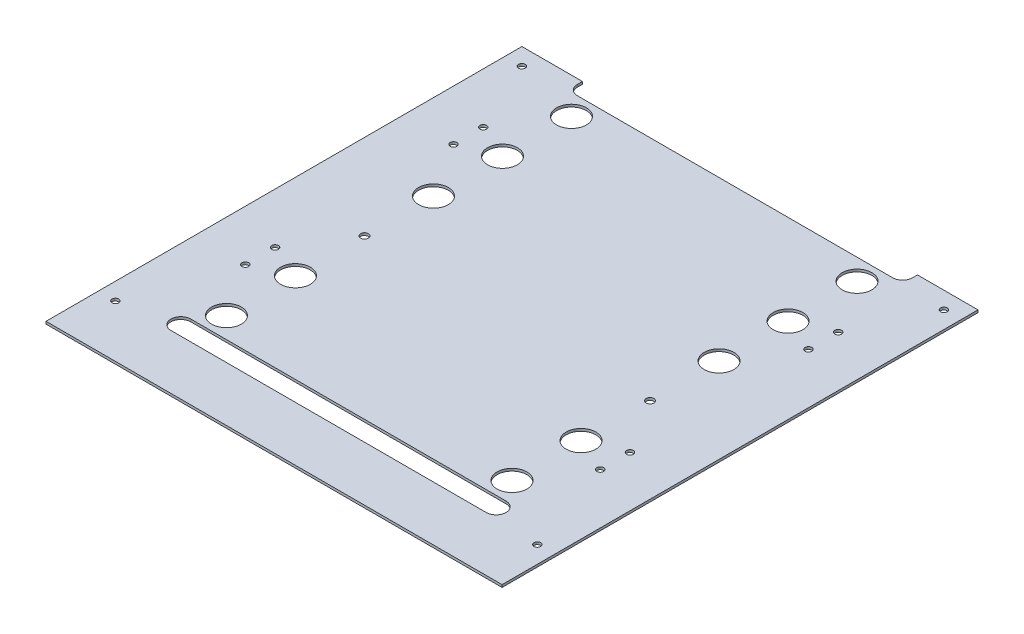
SolidWorks part; units mm, degrees
material "PC High Viscosity"
ref_plane "Front Plane" through (0, 0, 0) normal (0, 0, 1) x (1, 0, 0)
ref_plane "Top Plane" through (0, 0, 0) normal (0, 1, 0) x (1, 0, 0)
ref_plane "Right Plane" through (0, 0, 0) normal (1, 0, 0) x (0, 0, -1)
sketch "Sketch1" plane through (0, 0, 0) normal (0, 1, 0) x (1, 0, 0)
  line L0 (-100.965, -111.125) -> (100.965, -111.125) construction
  line L1 (-146.05, 152.4) -> (146.05, 152.4)
  line L2 (-146.05, 152.4) -> (-146.05, -152.4)
  line L3 (-146.05, -152.4) -> (146.05, -152.4)
  line L4 (146.05, 152.4) -> (146.05, -152.4)
  line L5 (-146.05, 152.4) -> (146.05, -152.4) construction
  line L6 (-146.05, -152.4) -> (146.05, 152.4) construction
  line L7 (-100.965, -104.775) -> (100.965, -104.775)
  line L8 (-100.965, -117.475) -> (100.965, -117.475)
  line L9 (-100.965, 149.225) -> (100.965, 149.225) construction
  line L10 (-100.965, 155.575) -> (100.965, 155.575)
  line L11 (-100.965, 142.875) -> (100.965, 142.875)
  line L12 (-107.315, 149.225) -> (-107.315, 155.575)
  line L13 (-107.315, 155.575) -> (-100.965, 155.575)
  line L14 (107.315, 149.225) -> (107.315, 155.575)
  line L15 (107.315, 155.575) -> (100.965, 155.575)
  line L16 (-135.128, 141.478) -> (135.128, 141.478) construction
  line L17 (-113.665, 95.25) -> (-113.665, 76.2) construction
  line L18 (-91.44, 41.148) -> (-91.44, -3.048) construction
  line L19 (91.44, 41.148) -> (91.44, -3.048) construction
  line L20 (-91.44, 19.05) -> (91.44, 19.05) construction
  line L21 (0, 149.225) -> (0, -111.125) construction
  arc A0 (-100.965, -104.775) -> (-100.965, -117.475) centre (-100.965, -111.125) ccw
  arc A1 (100.965, -117.475) -> (100.965, -104.775) centre (100.965, -111.125) ccw
  arc A2 (-100.965, 155.575) -> (-100.965, 142.875) centre (-100.965, 149.225) ccw
  arc A3 (100.965, 142.875) -> (100.965, 155.575) centre (100.965, 149.225) ccw
  circle A4 centre (-135.128, 141.478) radius 2.1527
  circle A5 centre (-135.128, -118.872) radius 2.1527
  circle A6 centre (135.128, 141.478) radius 2.1527
  circle A7 centre (135.128, -118.872) radius 2.1527
  circle A8 centre (-91.44, 129.54) radius 9.525
  circle A9 centre (91.44, 129.54) radius 9.525
  circle A10 centre (91.44, 85.344) radius 9.525
  circle A11 centre (-91.44, 85.344) radius 9.525
  circle A12 centre (91.44, 41.148) radius 9.525
  circle A13 centre (-91.44, 41.148) radius 9.525
  circle A14 centre (91.44, -3.048) radius 9.525 construction
  circle A15 centre (-91.44, -3.048) radius 9.525 construction
  circle A16 centre (91.44, -47.244) radius 9.525
  circle A17 centre (-91.44, -47.244) radius 9.525
  circle A18 centre (91.44, -91.44) radius 9.525
  circle A19 centre (-91.44, -91.44) radius 9.525
  circle A20 centre (-91.44, -3.048) radius 2.4892
  circle A21 centre (91.44, -3.048) radius 2.4892
  circle A22 centre (-113.665, 95.25) radius 2.1527
  circle A23 centre (-113.665, 76.2) radius 2.1527
  circle A24 centre (-113.665, -38.1) radius 2.1527
  circle A25 centre (-113.665, -57.15) radius 2.1527
  circle A26 centre (113.665, -57.15) radius 2.1527
  circle A27 centre (113.665, -38.1) radius 2.1527
  circle A28 centre (113.665, 76.2) radius 2.1527
  circle A29 centre (113.665, 95.25) radius 2.1527
  point P0 (0, 0)
  point P8 (0, -111.125)
  point P13 (0, -111.125)
  point P14 (0, -152.4)
  point P17 (0, 149.225)
  point P37 (0, 141.478)
  point P83 (0, 0)
  point P84 (-113.665, 92.0897)
  dimension "D4" = 6.35
  dimension "D9" = 4.3053
  dimension "D11" = 19.05
  dimension "D17" = 4.9784
  dimension "D18" = 4.3053
  dimension "D1" = 292.1
  dimension "D2" = 304.8
  dimension "D3" = 45.085
  dimension "D5" = 41.275
  dimension "D6" = 3.175
  dimension "D7" = 10.922
  dimension "D8" = 10.922
  dimension "D10" = 33.528
  dimension "D12" = 54.61
  dimension "D13" = 22.86
  dimension "D14" = 54.61
  dimension "D16" = 44.196
  dimension "D19" = 22.225
  dimension "D20" = 19.05
  dimension "D21" = 9.906
  dimension "D15" = 6
extrude "Boss-Extrude1" add sketch "Sketch1" along normal blind 1.5875 contours A3 L11 A2 L12 L1 L2 L3 L4 L14 A1 L8 A0 L7
